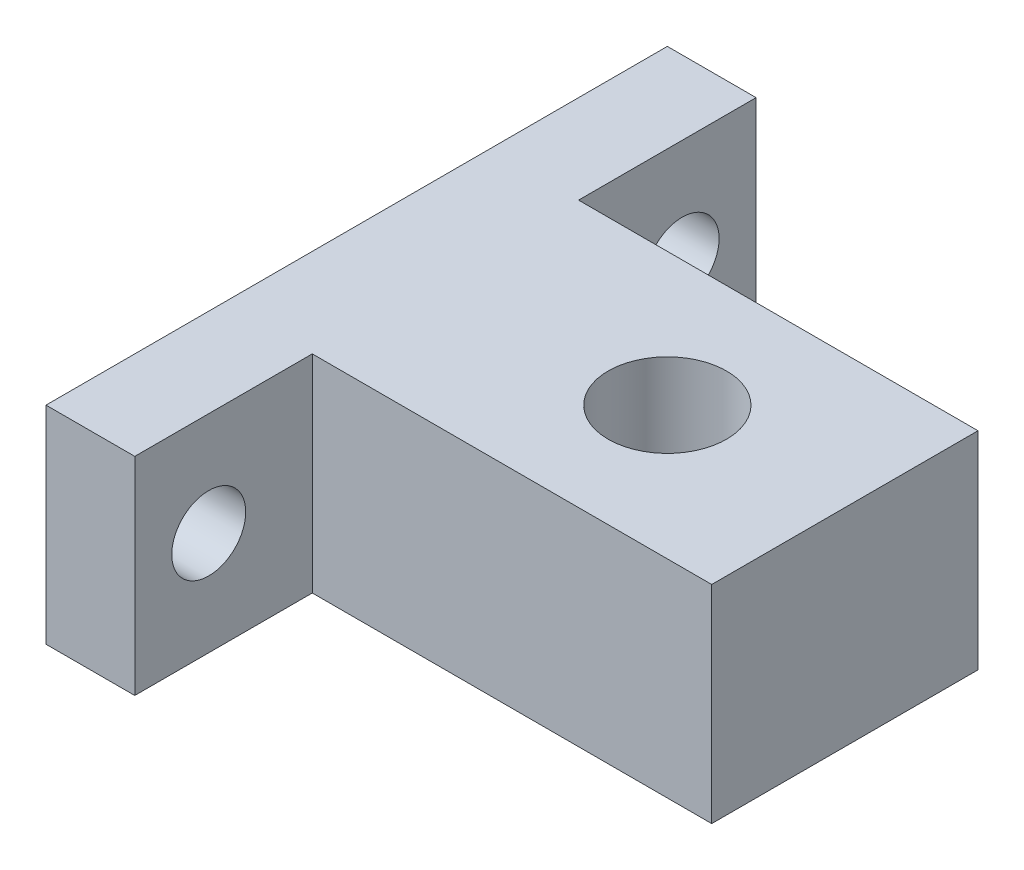
SolidWorks part; units mm, degrees
ref_plane "前视基准面" through (0, 0, 0) normal (0, 0, 1) x (1, 0, 0)
ref_plane "上视基准面" through (0, 0, 0) normal (0, 1, 0) x (1, 0, 0)
ref_plane "右视基准面" through (0, 0, 0) normal (1, 0, 0) x (0, 0, -1)
sketch "草图1" plane through (0, 0, 0) normal (0, 1, 0) x (1, 0, 0)
  line L0 (3, -21) -> (3, -9)
  line L1 (3, 21) -> (-3, 21)
  line L2 (3, 21) -> (3, 9)
  line L3 (3, -21) -> (-3, -21)
  line L4 (-3, 21) -> (-3, -21)
  line L5 (3, 21) -> (-3, -21) construction
  line L6 (3, -21) -> (-3, 21) construction
  line L7 (3, -9) -> (30, -9)
  line L8 (3, 9) -> (30, 9)
  line L9 (30, -9) -> (30, 9)
  circle A0 centre (18, 0) radius 4
  point P0 (0, 0)
extrude "凸台-拉伸1" add sketch "草图1" along normal blind 14
sketch "草图2" plane through (3, 0, 0) normal (1, 0, 0) x (0, 0, -1)
  line L0 (-21, 14) -> (-9, 14) construction
  line L1 (-21, 14) -> (-21, 0) construction
  line L2 (21, 14) -> (21, 0) construction
  line L3 (9, 0) -> (21, 0) construction
  circle A0 centre (-16, 7) radius 2.5
  circle A1 centre (16, 7) radius 2.5
  point P10 (21, 7)
  dimension "D2" = 5
  dimension "D3" = 5
  dimension "D4" = 7
  dimension "D1" = 7
extrude "切除-拉伸1" cut sketch "草图2" against normal blind 10
